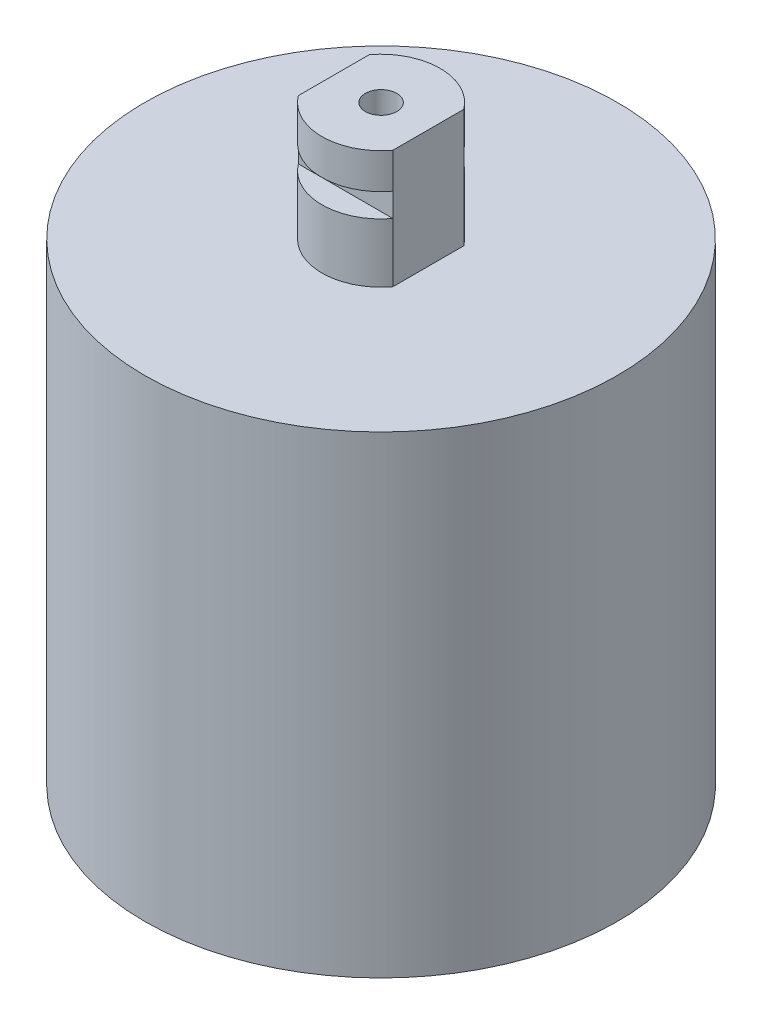
SolidWorks part; units mm, degrees
ref_plane "Front Plane" through (0, 0, 0) normal (0, 0, 1) x (1, 0, 0)
ref_plane "Top Plane" through (0, 0, 0) normal (0, 1, 0) x (1, 0, 0)
ref_plane "Right Plane" through (0, 0, 0) normal (1, 0, 0) x (0, 0, -1)
sketch "Sketch1" plane through (0, 0, 0) normal (0, 1, 0) x (1, 0, 0)
  circle A0 centre (0, 0) radius 60
  dimension "D1" = 120
extrude "Boss-Extrude1" add sketch "Sketch1" against normal blind 120
sketch "Sketch2" plane through (0, 0, 0) normal (0, 1, 0) x (1, 0, 0)
  line L0 (0, -15) -> (0, 15) construction
  line L1 (-12, 9) -> (12, 9) construction
  line L2 (-12, -9) -> (12, -9) construction
  line L3 (-12, 9) -> (-12, -9)
  line L4 (12, -9) -> (12, 9)
  arc A0 (-12, -9) -> (12, -9) centre (0, 0) ccw
  arc A1 (12, 9) -> (-12, 9) centre (0, 0) ccw
  dimension "D1" = 30
  dimension "D2" = 12
extrude "Boss-Extrude2" add sketch "Sketch2" along normal blind 30
sketch "Sketch3" plane through (12, 0, 0) normal (1, 0, 0) x (0, 0, -1)
  line L0 (-9, 30) -> (-9, 0) construction
  line L1 (-9, 15) -> (-15, 15)
  line L2 (-9, 15) -> (-9, 21)
  line L3 (-9, 21) -> (-15, 21)
  line L4 (-15, 15) -> (-15, 21)
  line L5 (-15, 30) -> (-15, 0) construction
  line L6 (-9, 30) -> (-15, 30) construction
  line L7 (0, 0) -> (0, 30) construction
  line L8 (-9, 0) -> (9, 0) construction
  line L9 (-9, 30) -> (9, 30) construction
  dimension "D1" = 6
  dimension "D2" = 9
extrude "Cut-Extrude1" cut sketch "Sketch3" against normal up to next
mirror "Mirror1" about plane through (0, 0, 0) normal (0, 0, 1) of "Cut-Extrude1"
sketch "Sketch4" plane through (0, 30, 0) normal (0, 1, 0) x (1, 0, 0)
  circle A0 centre (0, 0) radius 4
  dimension "D1" = 8
extrude "Cut-Extrude2" cut sketch "Sketch4" against normal blind 30
